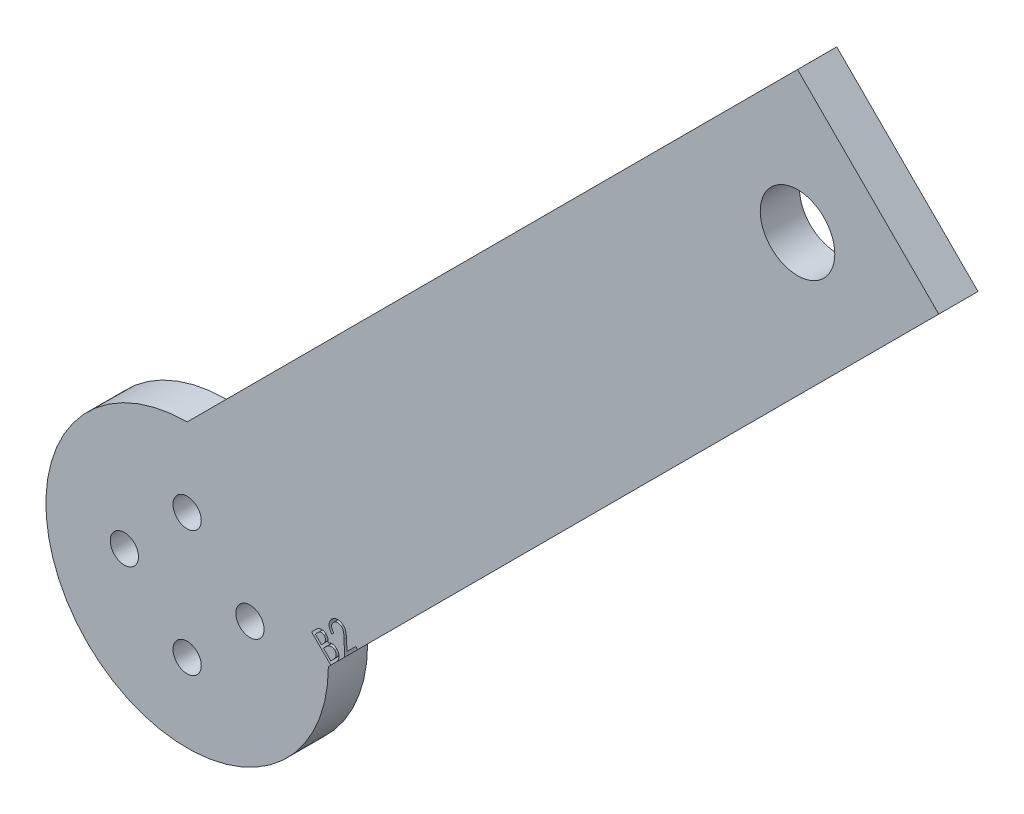
SolidWorks part; units mm, degrees
ref_plane "正面" through (0, 0, 0) normal (0, 0, 1) x (1, 0, 0)
ref_plane "平面" through (0, 0, 0) normal (0, 1, 0) x (1, 0, 0)
ref_plane "右側面" through (0, 0, 0) normal (1, 0, 0) x (0, 0, -1)
sketch "ｽｹｯﾁ2" plane through (0, 0, 0) normal (0, 0, 1) x (1, 0, 0)
  line L0 (0, 18) -> (77.7817, 95.7817)
  line L1 (18, 0) -> (95.7817, 77.7817)
  line L2 (95.7817, 77.7817) -> (77.7817, 95.7817)
  arc A0 (0, 18) -> (18, 0) centre (0, 0) ccw
  dimension "D1" = 18
  dimension "D2" = 110
extrude "ﾎﾞｽ - 押し出し1" add sketch "ｽｹｯﾁ2" along normal blind 5
sketch3d "3Dｽｹｯﾁ1"
  point P0 (7.7776, 13.9967, 5)
sketch3d "3Dｽｹｯﾁ2"
  point P0 (14.2826, 14.7063, 5)
ref_plane "平面2" through (0, 0, 5) normal (0, 0, 1) x (1, 0, 0)
sketch "ｽｹｯﾁ3" plane through (0, 0, 5) normal (0, 0, 1) x (1, 0, 0)
  circle A0 centre (8, 0) radius 1.8
  circle A1 centre (-8, 0) radius 1.8
  circle A2 centre (0, 8) radius 1.8
  circle A3 centre (0, -8) radius 1.8
extrude "ｶｯﾄ - 押し出し1" cut sketch "ｽｹｯﾁ3" against normal blind 5
sketch "ｽｹｯﾁ10" plane through (0, 0, 0) normal (0, 0, 1) x (1, 0, 0)
  line L0 (86.7817, 86.7817) -> (-12.7279, -12.7279) construction
  line L1 (95.7817, 77.7817) -> (77.7817, 95.7817) construction
  arc A0 (0, 18) -> (18, 0) centre (0, 0) ccw construction
sketch "ｽｹｯﾁ17" plane through (0, 0, 0) normal (0, 0, -1) x (-1, 0, 0)
  line L0 (0, 0) -> (-77.7817, 77.7817) construction
  line L1 (-86.7817, 86.7817) -> (12.7279, -12.7279) construction
  circle A0 centre (-77.7817, 77.7817) radius 4.75
  dimension "D2" = 9.5
  dimension "D1" = 110
extrude "ｶｯﾄ - 押し出し3" cut sketch "ｽｹｯﾁ17" against normal blind 10
sketch "ｽｹｯﾁ19" plane through (0, 0, 5) normal (0, 0, 1) x (1, 0, 0)
  text T0 "B2"
extrude "ｶｯﾄ - 押し出し4" cut sketch "ｽｹｯﾁ19" against normal blind 2
